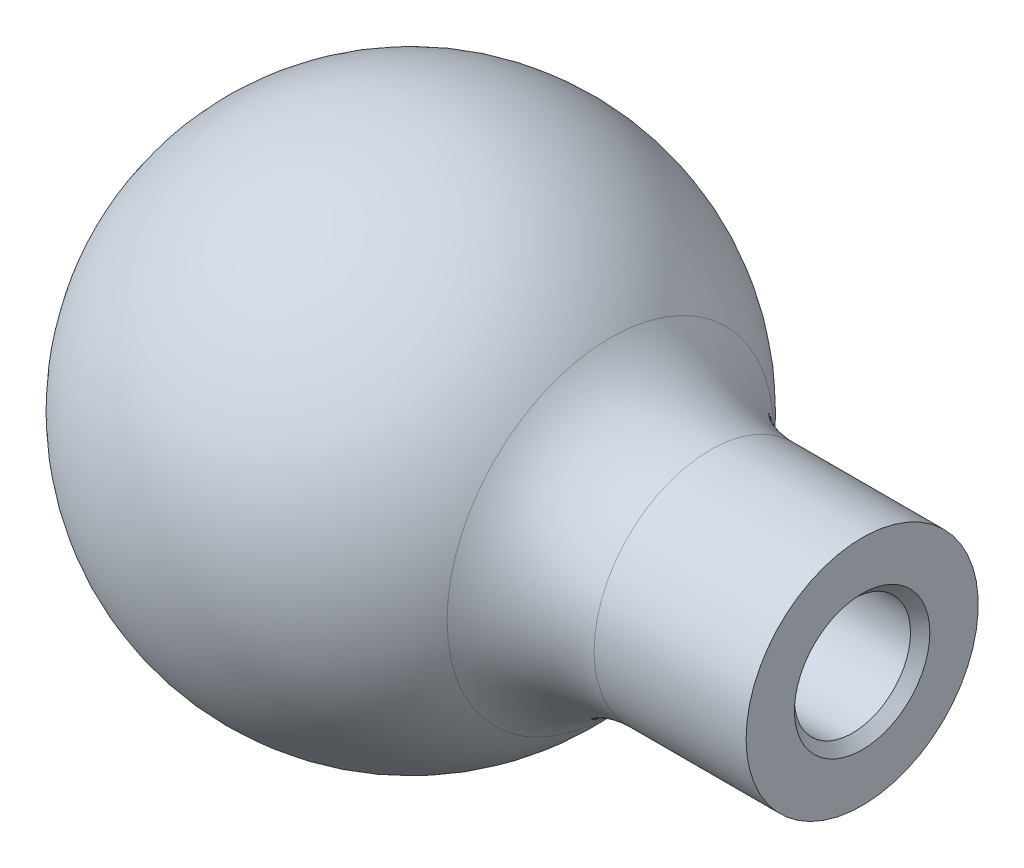
SolidWorks part; units mm, degrees
material "Nylon 101"
ref_plane "Front Plane" through (0, 0, 0) normal (0, 0, 1) x (1, 0, 0)
ref_plane "Top Plane" through (0, 0, 0) normal (0, 1, 0) x (1, 0, 0)
ref_plane "Right Plane" through (0, 0, 0) normal (1, 0, 0) x (0, 0, -1)
sketch "Sketch1" plane through (0, 0, 0) normal (0, 0, 1) x (1, 0, 0)
  line L0 (-20, 0) -> (35, 0)
  line L1 (0, 0) -> (22326.8689, 0) construction
  line L2 (35, 0) -> (35, 9)
  line L3 (35, 9) -> (17.8606, 9)
  arc A0 (17.8606, 9) -> (-20, 0) centre (0, 0) ccw
  dimension "D1" = 20
  dimension "D2" = 18
  dimension "D3" = 55
revolve "Revolve1" add sketch "Sketch1" angle 360 about L1
fillet "Fillet1" radius 10 1 edges at (17.8606, 0, 9)
hole_wizard "M10x1.0 Tapped Hole1" positions "Sketch2" profile "Sketch3" tap size "M10x1.0" standard "ANSI Metric"
sketch "Sketch2" plane through (35, 0, 0) normal (1, 0, 0) x (0, 0, -1)
  point P0 (0, 0)
sketch "Sketch3" plane through (35, 0, 0) normal (0, 1, 0) x (0, 0, -1)
  line L0 (0, 0) -> (0, 27.7039)
  line L1 (0, 27.7039) -> (4.5, 25)
  line L2 (4.5, 25) -> (4.5, 0.75)
  line L3 (4.5, 0.75) -> (5.25, 0)
  line L5 (5.25, 0) -> (0, 0)
  line L6 (-4.5, 0.75) -> (-5.25, 0) construction
  line L10 (0, 27.7039) -> (-4.5, 25) construction
  line L11 (0, -6.35) -> (0, 107.95) construction
  dimension "Tap Drill Dia." = 9
  dimension "Tap Drill Depth" = 25
  dimension "Near C'Sink Dia." = 10.5
  dimension "Near C'Sink Angle" = 90
  dimension "Drill Angle" = 118
cosmetic thread "Hole Thread2" parameters "D1"=20, "D2"=10
